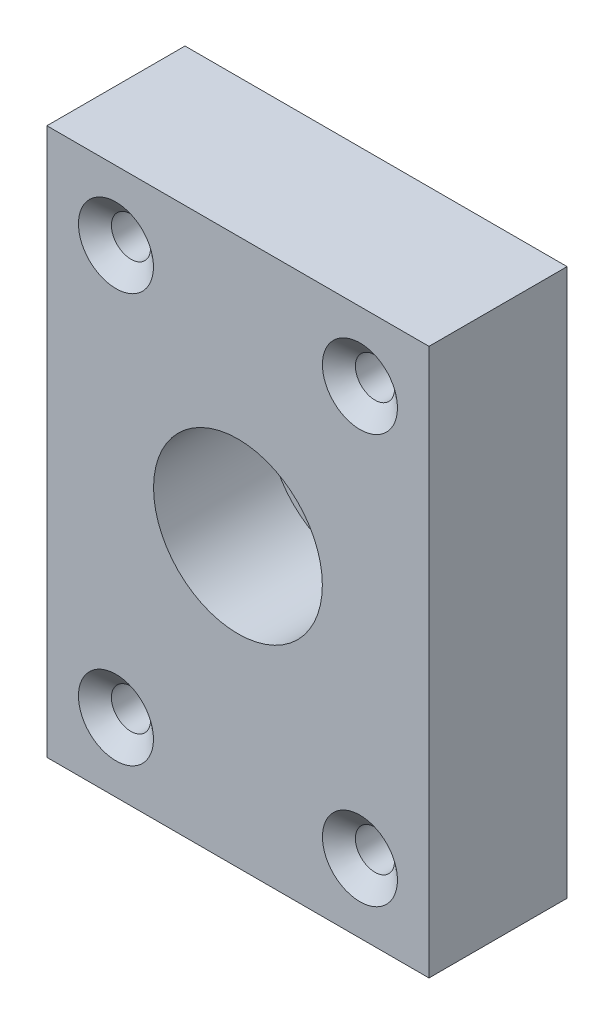
SolidWorks part; units mm, degrees
material "Beech"
ref_plane "Front Plane" through (0, 0, 0) normal (0, 0, 1) x (1, 0, 0)
ref_plane "Top Plane" through (0, 0, 0) normal (0, 1, 0) x (1, 0, 0)
ref_plane "Right Plane" through (0, 0, 0) normal (1, 0, 0) x (0, 0, -1)
sketch "Sketch1" plane through (0, 0, 0) normal (0, 0, 1) x (1, 0, 0)
  line L1 (0, 0) -> (49.8, 0)
  line L2 (0, 0) -> (0, 71.3)
  line L3 (0, 71.3) -> (49.8, 71.3)
  line L4 (49.8, 0) -> (49.8, 71.3)
  dimension "D1" = 71.3
  dimension "D2" = 49.8
extrude "base" add sketch "Sketch1" along normal blind 18
sketch "Sketch2" plane through (0, 0, 18) normal (0, 0, 1) x (1, 0, 0)
  line L0 (24.9, 37.4) -> (24.9, 0) construction
  line L1 (0, 0) -> (49.8, 0) construction
  circle A0 centre (24.9, 37.4) radius 11
  dimension "D1" = 22
  dimension "D2" = 37.4
extrude "lead nut inlay" cut sketch "Sketch2" against normal blind 15
sketch "Sketch3" plane through (0, 0, 3) normal (0, 0, 1) x (1, 0, 0)
  circle A0 centre (24.9, 37.4) radius 6.5
  circle A1 centre (24.9, 37.4) radius 11 construction
  dimension "D1" = 13
extrude "lead screw clearance" cut sketch "Sketch3" against normal through all
hole_wizard "woodscrew clearance" positions "Sketch4" profile "Sketch5" countersink size "#10" standard "ANSI Inch" end condition through all
sketch "Sketch4" plane through (0, 0, 18) normal (0, 0, 1) x (1, 0, 0)
  line L1 (9, 9) -> (40.8, 9)
  line L2 (9, 9) -> (9, 62.3)
  line L3 (9, 62.3) -> (40.8, 62.3)
  line L4 (40.8, 9) -> (40.8, 62.3)
  line L5 (24.9, 62.3) -> (24.9, 71.3)
  line L6 (49.8, 71.3) -> (0, 71.3) construction
  line L7 (9, 35.65) -> (0, 35.65)
  line L8 (0, 71.3) -> (0, 0) construction
  point P1 (9, 9)
  point P2 (40.8, 62.3)
  point P185 (9, 62.3)
  point P186 (40.8, 9)
  dimension "D1" = 9
sketch "Sketch5" plane through (9, 9, 18) normal (1, 0, 0) x (0, -1, 0)
  line L0 (0, 0) -> (0, 18)
  line L1 (0, 18) -> (2.5527, 18)
  line L2 (2.5527, 18) -> (2.5527, 1.9608)
  line L3 (2.5527, 1.9608) -> (4.8895, 0)
  line L5 (4.8895, 0) -> (0, 0)
  line L6 (-2.5527, 1.9608) -> (-4.8895, 0) construction
  line L11 (0, -6.35) -> (0, 107.95) construction
  dimension "Thru Hole Dia." = 5.1054
  dimension "Thru Hole Depth" = 18
  dimension "Near C'Sink Dia." = 9.779
  dimension "Near C'Sink Angle" = 100
